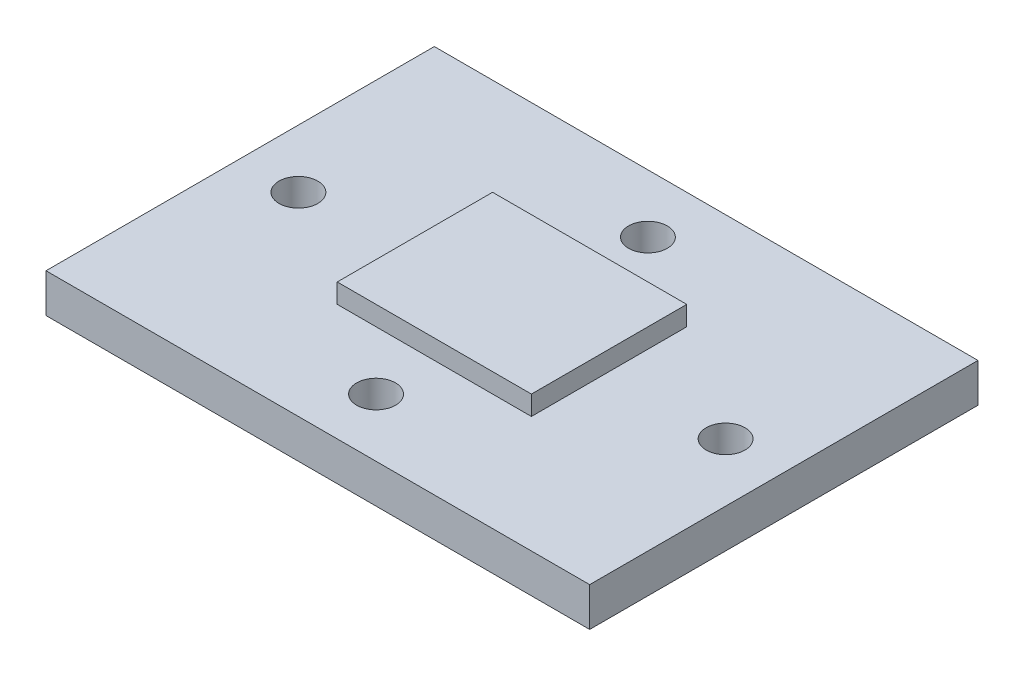
SolidWorks part; units mm, degrees
ref_plane "前视基准面" through (0, 0, 0) normal (0, 0, 1) x (1, 0, 0)
ref_plane "上视基准面" through (0, 0, 0) normal (0, 1, 0) x (1, 0, 0)
ref_plane "右视基准面" through (0, 0, 0) normal (1, 0, 0) x (0, 0, -1)
other "Configuration Table"
sketch "草图1" plane through (0, 646, 0) normal (0, 1, 0) x (1, 0, 0)
  line L1 (-580.5399, 225.1044) -> (-440.5399, 225.1044)
  line L2 (-580.5399, 225.1044) -> (-580.5399, 125.1044)
  line L3 (-580.5399, 125.1044) -> (-440.5399, 125.1044)
  line L4 (-440.5399, 225.1044) -> (-440.5399, 125.1044)
  circle A0 centre (-565.5399, 175.1044) radius 5
  circle A1 centre (-510.5399, 210.1044) radius 5
  circle A2 centre (-510.5399, 140.1044) radius 5
  circle A3 centre (-455.5399, 175.1044) radius 5
extrude "凸台-拉伸1" add sketch "草图1" along normal blind 10
ref_plane "基准面1" through (0, 706, 0) normal (0, 1, 0) x (1, 0, 0)
ref_plane "基准面2" through (0, 0, -175.1044) normal (0, 0, 1) x (1, 0, 0)
sketch "草图5" plane through (0, 656, 0) normal (0, 1, 0) x (1, 0, 0)
  line L0 (-565.5399, 175.1044) -> (-455.5399, 175.1044) construction
  line L1 (-535.5399, 195.1044) -> (-485.5399, 195.1044)
  line L2 (-535.5399, 195.1044) -> (-535.5399, 155.1044)
  line L3 (-535.5399, 155.1044) -> (-485.5399, 155.1044)
  line L4 (-485.5399, 195.1044) -> (-485.5399, 155.1044)
  line L5 (-510.5399, 210.1044) -> (-510.5399, 140.1044) construction
  dimension "D1" = 25
  dimension "D2" = 20
  dimension "D3" = 25
  dimension "D4" = 20
extrude "凸台-拉伸2" add sketch "草图5" along normal blind 5
